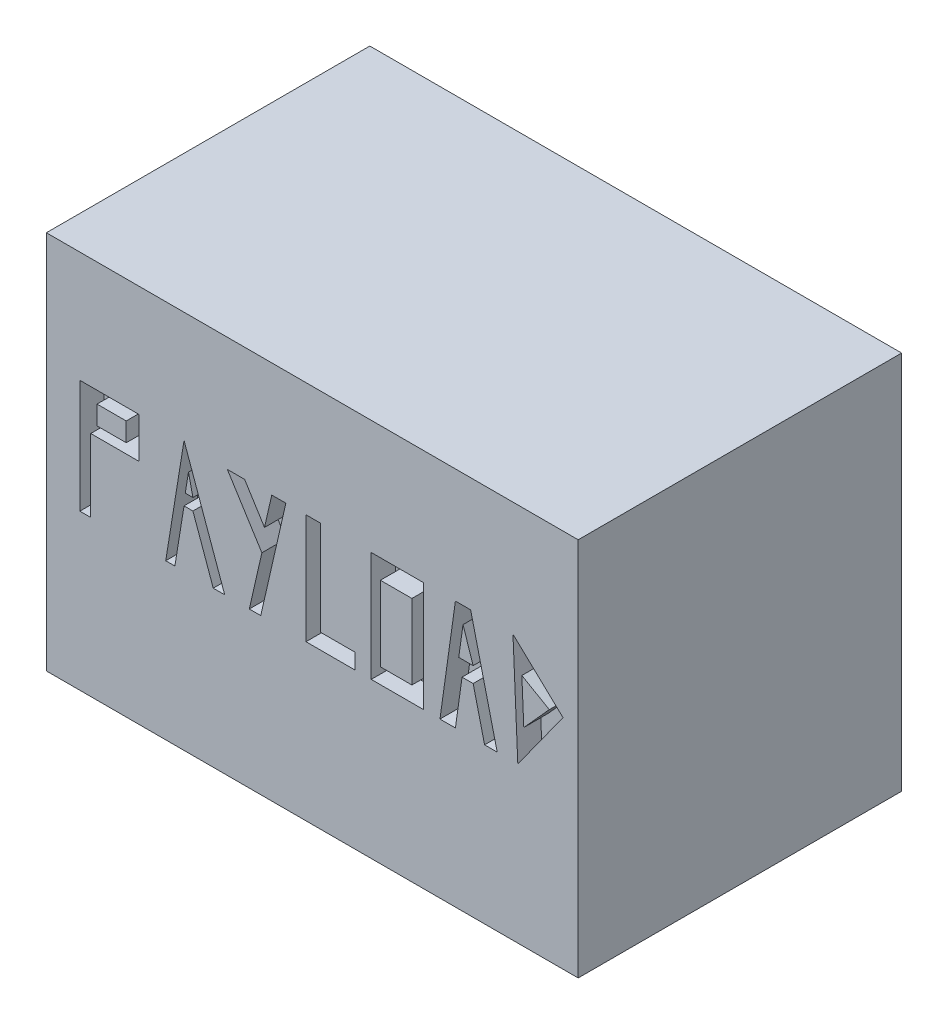
SolidWorks part; units mm, degrees
ref_plane "Front Plane" through (0, 0, 0) normal (0, 0, 1) x (1, 0, 0)
ref_plane "Top Plane" through (0, 0, 0) normal (0, 1, 0) x (1, 0, 0)
ref_plane "Right Plane" through (0, 0, 0) normal (1, 0, 0) x (0, 0, -1)
sketch "Sketch1" plane through (0, 0, 0) normal (0, 0, 1) x (1, 0, 0)
  line L1 (-279.4, 199.39) -> (279.4, 199.39)
  line L2 (-279.4, 199.39) -> (-279.4, -199.39)
  line L3 (-279.4, -199.39) -> (279.4, -199.39)
  line L4 (279.4, 199.39) -> (279.4, -199.39)
  line L5 (-279.4, 199.39) -> (279.4, -199.39) construction
  line L6 (-279.4, -199.39) -> (279.4, 199.39) construction
  point P0 (0, 0)
  dimension "D1" = 558.8
  dimension "D2" = 398.78
extrude "Boss-Extrude1" add sketch "Sketch1" against normal blind 339.852
sketch "Sketch2" plane through (0, 0, 0) normal (0, 0, 1) x (1, 0, 0)
  line L0 (-244.2267, 82.7122) -> (-244.2267, -36.3934)
  line L1 (-244.2267, 82.7122) -> (-182.2677, 82.7122)
  line L2 (-182.2677, 82.7122) -> (-182.2677, 40.0026)
  line L3 (-182.2677, 40.0026) -> (-232.7973, 40.0026)
  line L4 (-232.7973, 40.0026) -> (-232.7973, -36.3934)
  line L5 (-232.7973, -36.3934) -> (-244.2267, -36.3934)
  line L6 (-226.1804, 70.0798) -> (-226.1804, 50.2289)
  line L7 (-226.1804, 50.2289) -> (-195.5016, 50.2289)
  line L8 (-195.5016, 50.2289) -> (-195.5016, 70.0798)
  line L9 (-195.5016, 70.0798) -> (-226.1804, 70.0798)
  line L10 (-153.9951, -36.3934) -> (-134.7457, 82.7122)
  line L11 (-134.7457, 82.7122) -> (-92.0362, -36.3934)
  line L12 (-92.0362, -36.3934) -> (-104.067, -36.3934)
  line L13 (-104.067, -36.3934) -> (-125.4218, 23.1594)
  line L14 (-125.4218, 23.1594) -> (-134.7457, 23.1594)
  line L15 (-134.7457, 23.1594) -> (-144.3704, -36.3934)
  line L16 (-144.3704, -36.3934) -> (-153.9951, -36.3934)
  line L17 (-130.0838, 56.2443) -> (-133.4544, 35.3887)
  line L18 (-133.4544, 35.3887) -> (-125.4218, 35.3887)
  line L19 (-125.4218, 35.3887) -> (-130.0838, 56.2443)
  line L20 (-27.7457, 79.1205) -> (-54.1389, -36.3934)
  line L21 (-54.1389, -36.3934) -> (-66.1698, -36.3934)
  line L22 (-66.1698, -36.3934) -> (-52.9732, 21.3635)
  line L23 (-52.9732, 21.3635) -> (-89.2457, 79.1205)
  line L24 (-89.2457, 79.1205) -> (-71.1095, 79.1205)
  line L25 (-71.1095, 79.1205) -> (-50.1939, 45.8165)
  line L26 (-50.1939, 45.8165) -> (-42.5844, 79.1205)
  line L27 (-42.5844, 79.1205) -> (-27.7457, 79.1205)
  line L28 (-6.617, 79.1205) -> (-6.617, -36.3934)
  line L29 (-6.617, -36.3934) -> (44.6834, -36.3934)
  line L30 (44.6834, -36.3934) -> (44.6834, -20.1517)
  line L31 (44.6834, -20.1517) -> (8.4216, -20.1517)
  line L32 (8.4216, -20.1517) -> (8.4216, 79.1205)
  line L33 (8.4216, 79.1205) -> (-6.617, 79.1205)
  line L34 (61.959, -36.3934) -> (61.959, 79.1205)
  line L35 (61.959, 79.1205) -> (116.6994, 79.1205)
  line L36 (116.6994, 79.1205) -> (116.6994, -36.3934)
  line L37 (116.6994, -36.3934) -> (61.959, -36.3934)
  line L38 (71.5837, 58.6505) -> (71.5837, -20.1517)
  line L39 (71.5837, -20.1517) -> (104.6686, -20.1517)
  line L40 (104.6686, -20.1517) -> (104.6686, 58.6505)
  line L41 (104.6686, 58.6505) -> (71.5837, 58.6505)
  line L42 (150.3859, 79.1205) -> (134.1442, -36.3934)
  line L43 (134.1442, -36.3934) -> (150.3859, -36.3934)
  line L44 (150.3859, -36.3934) -> (157.3865, 13.3962)
  line L45 (157.3865, 13.3962) -> (169.0337, 13.3962)
  line L46 (169.0337, 13.3962) -> (181.0646, -36.3934)
  line L47 (181.0646, -36.3934) -> (194.2986, -36.3934)
  line L48 (194.2986, -36.3934) -> (166.3865, 79.1205)
  line L49 (166.3865, 79.1205) -> (150.3859, 79.1205)
  line L50 (158.3862, 61.6582) -> (153.8862, 29.6535)
  line L51 (153.8862, 29.6535) -> (169.0337, 29.6535)
  line L52 (169.0337, 29.6535) -> (158.3862, 61.6582)
  line L53 (210.8747, 79.1205) -> (215.9541, -36.3934)
  line L54 (215.9541, -36.3934) -> (263.4761, 29.6535)
  line L55 (263.4761, 29.6535) -> (210.8747, 79.1205)
  line L56 (220.2079, 46.3267) -> (222.245, 0)
  line L57 (222.245, 0) -> (249.039, 29.6535)
  line L58 (249.039, 29.6535) -> (220.2079, 46.3267)
extrude "Cut-Extrude1" cut sketch "Sketch2" against normal blind 25.4
